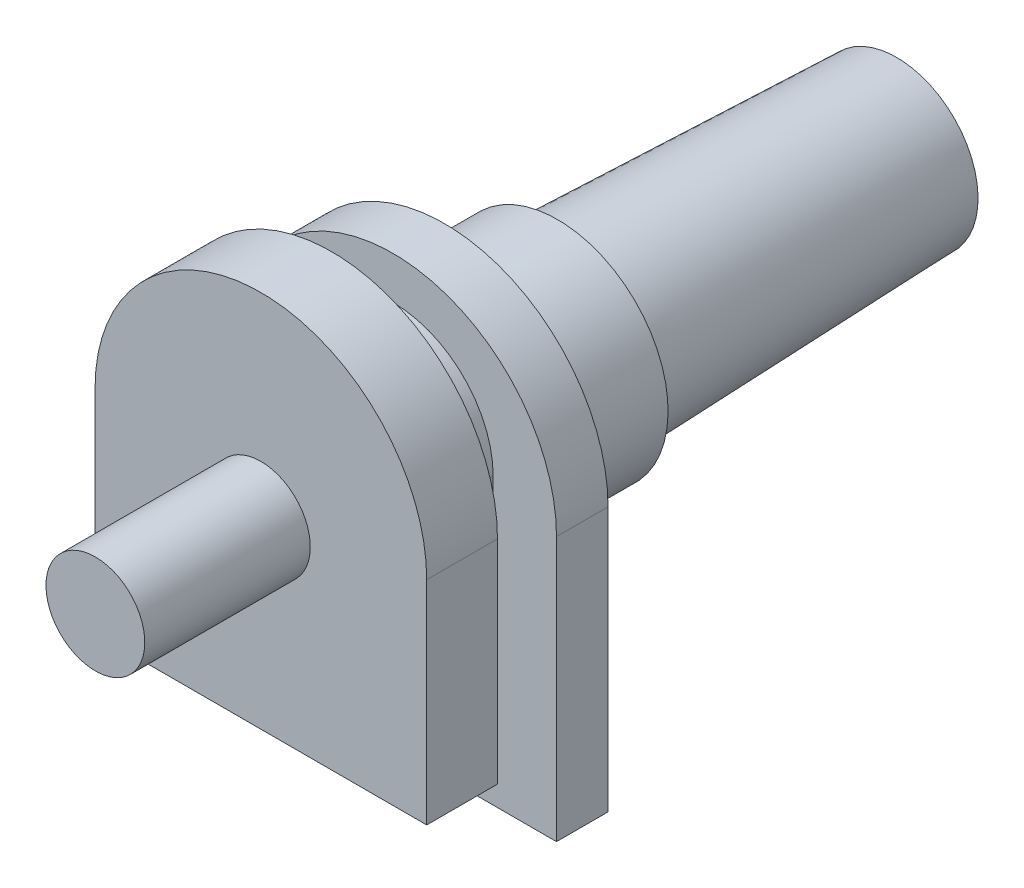
SolidWorks part; units mm, degrees
ref_plane "Front Plane" through (0, 0, 0) normal (0, 0, 1) x (1, 0, 0)
ref_plane "Top Plane" through (0, 0, 0) normal (0, 1, 0) x (1, 0, 0)
ref_plane "Right Plane" through (0, 0, 0) normal (1, 0, 0) x (0, 0, -1)
sketch "Sketch1" plane through (0, 0, 0) normal (0, 0, 1) x (1, 0, 0)
  line L0 (-7.335, 0) -> (-7.335, -9.395)
  line L1 (-7.335, -9.395) -> (7.335, -9.395)
  line L2 (7.335, -9.395) -> (7.335, 0)
  arc A0 (7.335, 0) -> (-7.335, 0) centre (0, 0) ccw
  dimension "D1" = 14.67
  dimension "D2" = 16.73
extrude "Boss-Extrude1" add sketch "Sketch1" along normal blind 3.13
sketch "Sketch2" plane through (0, 0, 0) normal (0, 0, -1) x (-1, 0, 0)
  line L3 (7.335, -9.395) -> (-7.335, -9.395) construction
  line L4 (-7.335, -9.395) -> (-7.335, 0) construction
  line L5 (7.335, 0) -> (7.335, -9.395) construction
  line L6 (0, 4.035) -> (0, 7.335) construction
  line L9 (-4.435, -0.4) -> (-4.435, -6.755)
  line L10 (-4.435, -6.755) -> (4.435, -6.755)
  line L11 (4.435, -6.755) -> (4.435, -0.4)
  arc A2 (7.335, 0) -> (-7.335, 0) centre (0, 0) ccw construction
  arc A3 (4.435, -0.4) -> (-4.435, -0.4) centre (0, -0.4) ccw
  dimension "D1" = 2.64
  dimension "D2" = 2.9
  dimension "D3" = 2.9
  dimension "D4" = 3.3
extrude "Boss-Extrude2" add sketch "Sketch2" along normal blind 2.71
sketch "Sketch3" plane through (0, 0, -2.71) normal (0, 0, -1) x (-1, 0, 0)
  line L0 (-7.235, -13.005) -> (7.235, -13.005)
  line L1 (7.235, -13.005) -> (7.235, -1.32)
  line L2 (-7.235, -1.32) -> (-7.235, -13.005)
  line L3 (7.335, -9.395) -> (-7.335, -9.395) construction
  line L4 (0, -13.005) -> (0, 0) construction
  line L5 (0, 5.915) -> (0, 7.335) construction
  arc A0 (7.235, -1.32) -> (-7.235, -1.32) centre (0, -1.32) ccw
  arc A1 (7.335, 0) -> (-7.335, 0) centre (0, 0) ccw construction
  dimension "D1" = 3.61
  dimension "D2" = 14.47
  dimension "D3" = 1.42
extrude "Boss-Extrude3" add sketch "Sketch3" along normal blind 2.28
sketch "Sketch5" plane through (0, 0, 0) normal (1, 0, 0) x (0, 0, -1)
  line L0 (4.99, 3.57) -> (9.99, 3.57)
  line L1 (4.99, -1.32) -> (4.99, 5.915) construction
  line L2 (9.99, 3.57) -> (9.99, 2.815)
  line L3 (9.99, 2.815) -> (24.99, 2.28)
  line L4 (24.99, 2.28) -> (24.99, -1.32)
  line L5 (24.99, -1.32) -> (4.99, -1.32)
  line L6 (4.99, -1.32) -> (4.99, 3.57)
  line L7 (24.99, -1.32) -> (27.3663, -1.32) construction
  point P11 (24.99, 0.48)
  dimension "D1" = 9.78
  dimension "D2" = 5
  dimension "D3" = 8.27
  dimension "D4" = 7.2
  dimension "D5" = 20
revolve "Revolve1" add sketch "Sketch5" angle 360 about L7
sketch "Sketch6" plane through (0, 0, 0) normal (1, 0, 0) x (0, 0, -1)
  line L0 (-3.13, 0.865) -> (-10.4502, 0.865)
  line L1 (-3.13, 7.335) -> (-3.13, 0) construction
  line L2 (-10.4502, 0.865) -> (-10.4502, -1.32)
  line L3 (-10.4502, -1.32) -> (-3.13, -1.32)
  line L4 (-3.13, -9.395) -> (-3.13, 0) construction
  line L5 (-3.13, -1.32) -> (-3.13, 0.865)
  line L6 (-10.4502, -1.32) -> (-17.4889, -1.32) construction
  line L7 (9.99, -1.32) -> (24.99, -1.32) construction
  dimension "D1" = 4.37
revolve "Revolve2" add sketch "Sketch6" angle 360 about L6
